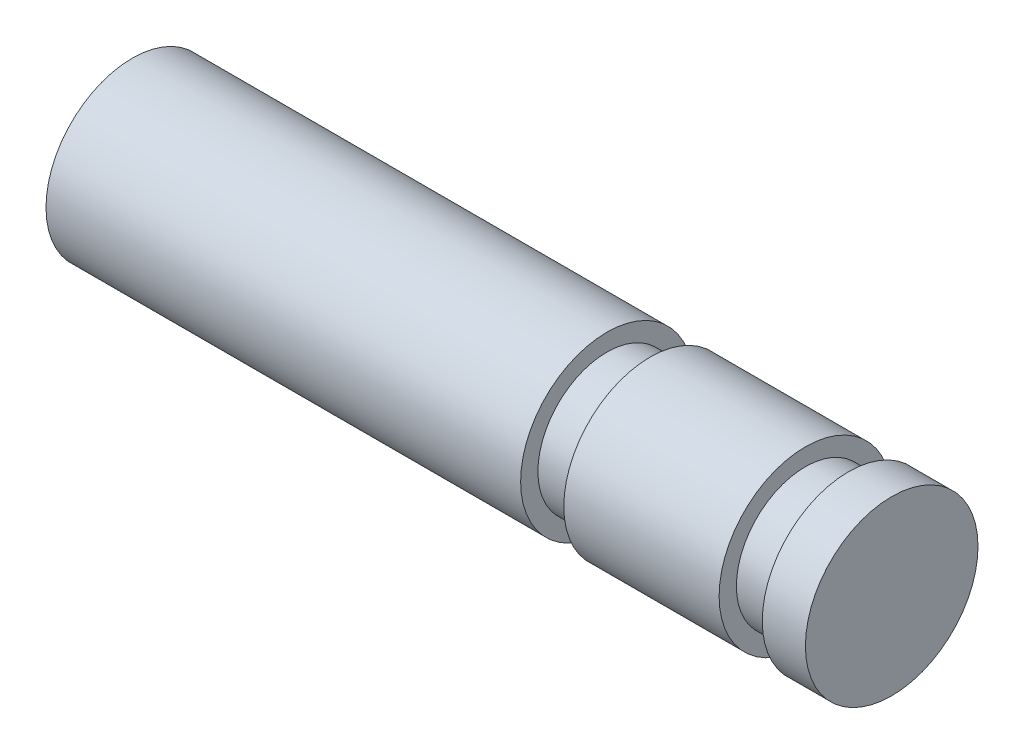
SolidWorks part; units mm, degrees
ref_plane "Front Plane" through (0, 0, 0) normal (0, 0, 1) x (1, 0, 0)
ref_plane "Top Plane" through (0, 0, 0) normal (0, 1, 0) x (1, 0, 0)
ref_plane "Right Plane" through (0, 0, 0) normal (1, 0, 0) x (0, 0, -1)
sketch "Sketch1" plane through (0, 0, 0) normal (0, 0, 1) x (1, 0, 0)
  line L0 (-31.2, 0) -> (31.7926, 0) construction
  line L1 (-31.2, 0) -> (-31.2, 4)
  line L2 (-31.2, 4) -> (-9.2, 4)
  line L3 (-9.2, 4) -> (-9.2, 3.2)
  line L4 (-9.2, 3.2) -> (-7.2, 3.2)
  line L5 (-7.2, 3.2) -> (-7.2, 4)
  line L6 (-7.2, 4) -> (0, 4)
  line L7 (0, 4) -> (0, 3.2)
  line L8 (0, 3.2) -> (2, 3.2)
  line L9 (2, 3.2) -> (2, 4)
  line L10 (2, 4) -> (4, 4)
  line L11 (4, 4) -> (4, 0)
  line L12 (4, 0) -> (-31.2, 0)
  line L13 (-31.2, 4) -> (2, 4) construction
  dimension "D1" = 8
  dimension "D2" = 2
  dimension "D3" = 2
  dimension "D4" = 7.2
  dimension "D5" = 2
  dimension "D6" = 22
  dimension "D7" = 0.8
  dimension "D8" = 0.8
revolve "Revolve1" add sketch "Sketch1" angle 360 about L0
